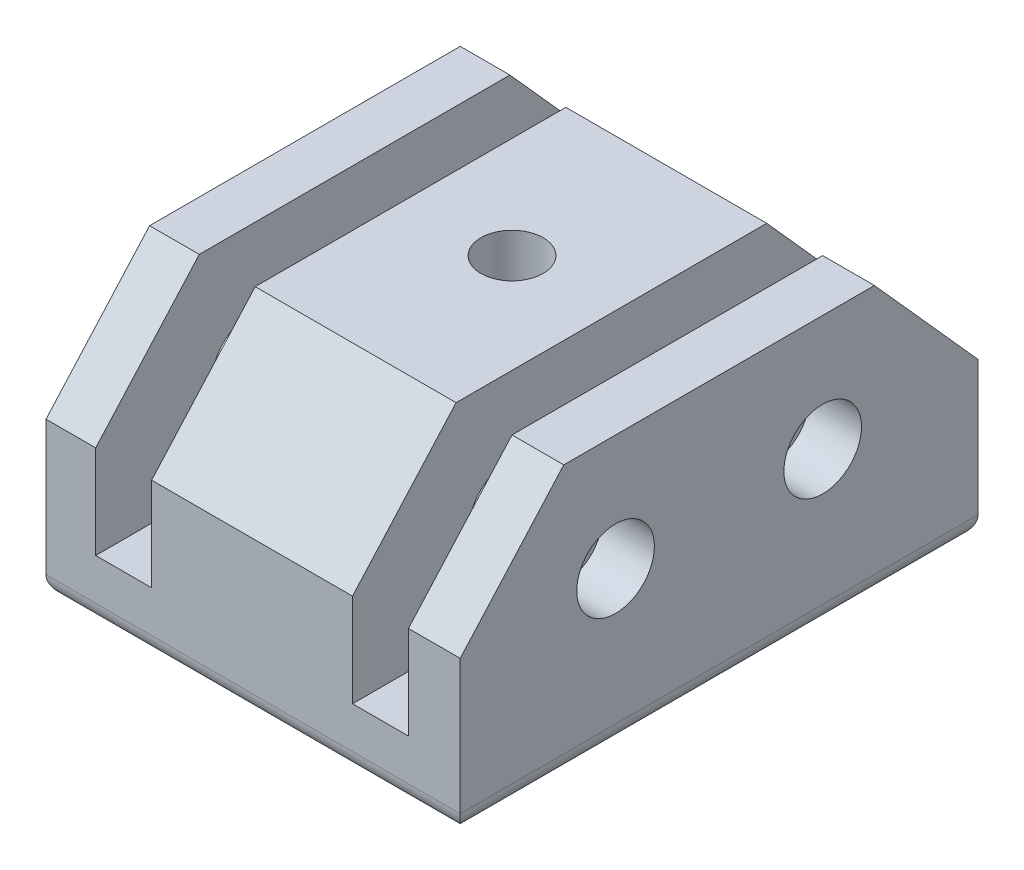
SolidWorks part; units mm, degrees
ref_plane "Front Plane" through (0, 0, 0) normal (0, 0, 1) x (1, 0, 0)
ref_plane "Top Plane" through (0, 0, 0) normal (0, 1, 0) x (1, 0, 0)
ref_plane "Right Plane" through (0, 0, 0) normal (1, 0, 0) x (0, 0, -1)
sketch "Sketch1" plane through (0, 0, 0) normal (1, 0, 0) x (0, 0, -1)
  line L1 (0, 0) -> (63.5, 0)
  line L2 (0, 0) -> (0, 6.35)
  line L3 (0, 6.35) -> (63.5, 6.35)
  line L4 (63.5, 0) -> (63.5, 6.35)
  dimension "D1" = 6.35
  dimension "D2" = 63.5
extrude "Boss-Extrude1" add sketch "Sketch1" against normal blind 50.8
sketch "Sketch2" plane through (0, 0, 0) normal (1, 0, 0) x (0, 0, -1)
  line L0 (0, 6.35) -> (0, 19.05)
  line L1 (0, 19.05) -> (12.7, 33.249)
  line L2 (12.7, 33.249) -> (50.8, 33.249)
  line L3 (50.8, 33.249) -> (63.5, 19.05)
  line L4 (63.5, 19.05) -> (63.5, 6.35)
  line L5 (63.5, 6.35) -> (0, 6.35)
  point P7 (31.75, 33.249)
  point P10 (31.75, 6.35)
  dimension "D1" = 38.1
  dimension "D2" = 12.7
  dimension "D3" = 12.7
  dimension "D4" = 19.05
  dimension "D5" = 19.05
extrude "Boss-Extrude2" add sketch "Sketch2" against normal blind 50.8
sketch "Sketch10" plane through (0, 0, -63.5) normal (0, 0, -1) x (-1, 0, 0)
  line L1 (50.8, 33.249) -> (0, 33.249) construction
  line L3 (6.35, 7.62) -> (6.35, 33.249)
  line L4 (6.35, 33.249) -> (13.208, 33.249)
  line L5 (13.208, 7.62) -> (13.208, 33.249)
  line L6 (6.35, 7.62) -> (13.208, 7.62)
  line L8 (50.8, 0) -> (0, 0) construction
  point P11 (13.208, 7.62)
  dimension "D1" = 7.62
  dimension "D2" = 6.858
  dimension "D3" = 6.35
extrude "Cut-Extrude1" cut sketch "Sketch10" against normal through all
pattern_linear "LPattern3" count 2 spacing 31.496 along (-1, 0, 0) of "Cut-Extrude1"
sketch "Sketch11" plane through (0, 0, 0) normal (1, 0, 0) x (0, 0, -1)
  circle A0 centre (19.05, 19.05) radius 4.7625
  circle A1 centre (19.05, 19.05) radius 7.9375 construction
  circle A2 centre (44.45, 19.05) radius 4.7625
  circle A3 centre (44.45, 19.05) radius 7.9375 construction
  dimension "D1" = 9.525
  dimension "D3" = 15.875
  dimension "D4" = 9.525
  dimension "D6" = 15.875
  dimension "D2" = 6.35
  dimension "D5" = 6.35
extrude "Cut-Extrude2" cut sketch "Sketch11" against normal through all
sketch "Sketch14" plane through (0, 33.249, 0) normal (0, 1, 0) x (1, 0, 0)
  line L3 (-37.846, 12.7) -> (-37.846, 50.8) construction
  point P0 (-25.4, 31.75)
  point P4 (-37.846, 31.75)
  dimension "D1" = 12.446
sketch "Sketch17" plane through (0, 40.0201, -44.7438) normal (0, 0.6667, -0.7454) x (-1, 0, 0)
  line L0 (13.208, -28.1343) -> (13.208, -9.0843) construction
  line L1 (37.846, -9.0843) -> (13.208, -9.0843) construction
  point P0 (25.527, -18.6093)
  point P4 (13.208, -18.6093)
  point P7 (25.527, -9.0843)
sketch "Sketch18" plane through (0, 8.4667, 9.466) normal (0, 0.6667, 0.7454) x (1, 0, 0)
  line L0 (-13.208, 33.249) -> (-13.208, 14.199) construction
  line L1 (-37.846, 33.249) -> (-13.208, 33.249) construction
  point P0 (-25.527, 23.724)
  point P1 (-25.527, 23.724)
  point P4 (-13.208, 23.724)
  point P7 (-25.527, 33.249)
ref_plane "Plane2" through (0, 33.02, 0) normal (0, -1, 0) x (-1, 0, 0)
fillet "Fillet1" radius 2.54 4 edges at (0, 0, -31.75) (-50.8, 0, -31.75) (-25.4, 0, 0) (-25.4, 0, -63.5)
sketch "Sketch24" plane through (0, 0, 0) normal (0, -1, 0) x (1, 0, 0)
  line L0 (-25.4, -63.5) -> (-25.4, 0) construction
  line L1 (-50.8, -63.5) -> (0, -63.5) construction
  line L2 (-50.8, 0) -> (0, 0) construction
  line L3 (0, -31.75) -> (-50.8, -31.75) construction
  line L4 (0, 0) -> (0, -63.5) construction
  line L5 (-50.8, 0) -> (-50.8, -63.5) construction
  circle A0 centre (-25.4, -31.75) radius 3.81
  dimension "D1" = 7.62
extrude "Cut-Extrude10" cut sketch "Sketch24" against normal through all
sketch "Sketch25" plane through (0, 0, 0) normal (0, -1, 0) x (1, 0, 0)
  line L1 (-29.3595, -24.892) -> (-33.3189, -31.75)
  line L2 (-33.3189, -31.75) -> (-29.3595, -38.608)
  line L3 (-29.3595, -38.608) -> (-21.4405, -38.608)
  line L4 (-21.4405, -38.608) -> (-17.4811, -31.75)
  line L5 (-17.4811, -31.75) -> (-21.4405, -24.892)
  line L6 (-21.4405, -24.892) -> (-29.3595, -24.892)
  circle A1 centre (-25.4, -31.75) radius 6.858 construction
extrude "Cut-Extrude11" cut sketch "Sketch25" against normal blind 6.35
